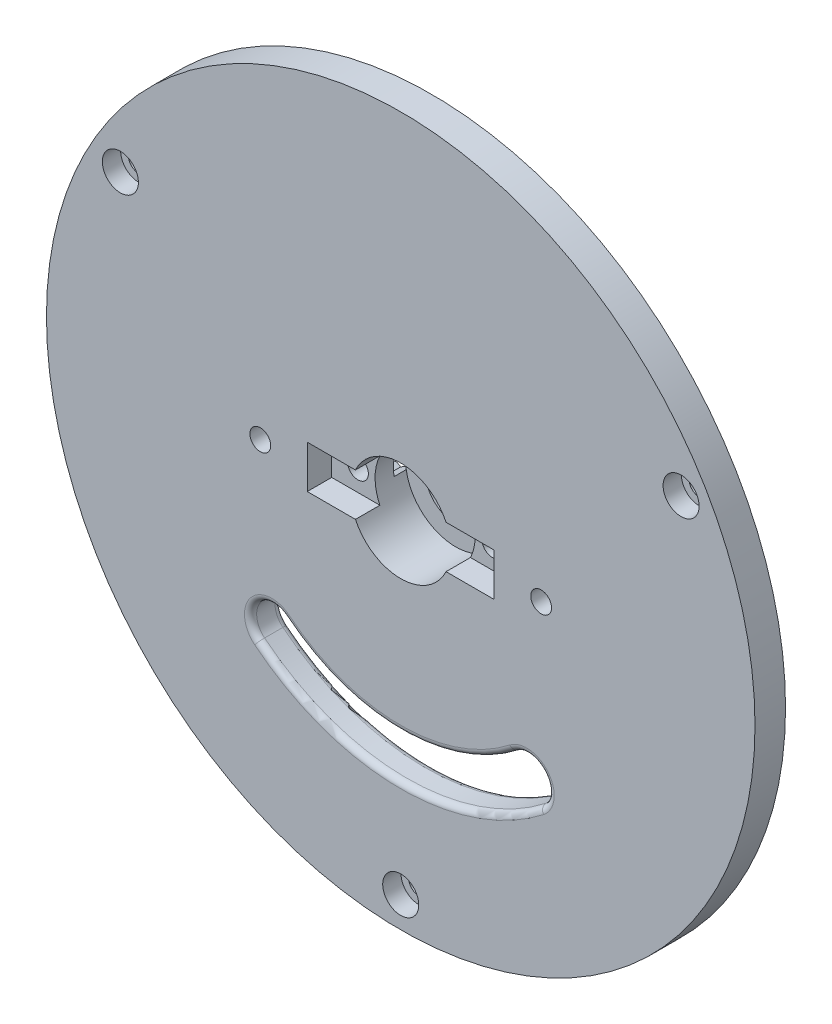
SolidWorks part; units mm, degrees
ref_plane "Front Plane" through (0, 0, 0) normal (0, 0, 1) x (1, 0, 0)
ref_plane "Top Plane" through (0, 0, 0) normal (0, 1, 0) x (1, 0, 0)
ref_plane "Right Plane" through (0, 0, 0) normal (1, 0, 0) x (0, 0, -1)
sketch "Sketch1" plane through (0, 0, 0) normal (0, 0, 1) x (1, 0, 0)
  line L0 (0, 0) -> (0, -68.2966) construction
  line L1 (0, 0) -> (-62.8311, 36.2756) construction
  circle A0 centre (0, 0) radius 8.2
  circle A1 centre (0, 53) radius 1.7 construction
  circle A2 centre (0, 0) radius 53 construction
  circle A3 centre (0, 0) radius 58
  circle A6 centre (0, -53) radius 1.7
  circle A7 centre (-45.8993, 26.5) radius 1.7
  circle A8 centre (45.8993, 26.5) radius 1.7
  circle A9 centre (-45.8993, 26.5) radius 1.7
  circle A10 centre (45.8993, 26.5) radius 1.7
  point P14 (0, 0)
  point P21 (0, 0)
  point P24 (0, 0)
  dimension "D1" = 16.4
  dimension "D2" = 106
  dimension "D3" = 3.4
  dimension "D4" = 5
  dimension "D5" = 120
  dimension "D6" = 3.4
  dimension "D8" = 106
  dimension "D7" = 3
  dimension "D9" = 3
extrude "Boss-Extrude1" add sketch "Sketch1" along normal blind 5
sketch "Sketch3" plane through (0, 0, 0) normal (0, 1, 0) x (1, 0, 0)
  line L0 (0, 0) -> (0, 9.41) construction
  line L2 (58, 0) -> (-58, 0) construction
  line L3 (-18, 0) -> (-12, 6)
  line L4 (-12, 6) -> (-5, 6)
  line L6 (-5, 6) -> (-5, 4)
  line L7 (-5, 4) -> (-8.2, 4)
  line L8 (-8.2, 4) -> (-8.2, 0)
  line L9 (-8.2, 0) -> (-18, 0)
  line L10 (-18.6622, -5) -> (0, -5)
  line L11 (-58, -5) -> (58, -5) construction
  dimension "D1" = 2
  dimension "D2" = 12
  dimension "D3" = 18
  dimension "D4" = 9
  dimension "D5" = 45
  dimension "D6" = 8.2
  dimension "D7" = 5
revolve "Revolve1" add sketch "Sketch3" angle 360 about L0
sketch "Sketch4" plane through (0, 0, 5) normal (0, 0, 1) x (1, 0, 0)
  line L1 (-15.3, 3.5) -> (15.3, 3.5)
  line L2 (-15.3, 3.5) -> (-15.3, -3.5)
  line L3 (-15.3, -3.5) -> (15.3, -3.5)
  line L4 (15.3, 3.5) -> (15.3, -3.5)
  line L5 (-15.3, 3.5) -> (15.3, -3.5) construction
  line L6 (-15.3, -3.5) -> (15.3, 3.5) construction
  point P0 (0, 0)
  dimension "D1" = 7
  dimension "D2" = 30.6
extrude "Cut-Extrude2" cut sketch "Sketch4" against normal blind 4
sketch "Sketch5" plane through (0, 0, -6) normal (0, 0, -1) x (-1, 0, 0)
  line L0 (-11, 0) -> (11, 0) construction
  line L1 (-13.9012, 1.675) -> (-11, 0) construction
  line L2 (-11, 0) -> (-8.0988, -1.675) construction
  line L3 (-13.9012, -1.675) -> (-8.0988, 1.675) construction
  line L4 (-11, -3.35) -> (-11, 3.35) construction
  line L11 (0, 0) -> (0, 11) construction
  line L18 (-11, 3.35) -> (-13.9012, 1.675)
  line L19 (-13.9012, 1.675) -> (-13.9012, -1.675)
  line L20 (-13.9012, -1.675) -> (-11, -3.35)
  line L21 (-11, -3.35) -> (-8.0988, -1.675)
  line L22 (-8.0988, -1.675) -> (-8.0988, 1.675)
  line L23 (-8.0988, 1.675) -> (-11, 3.35)
  line L24 (8.0988, -1.675) -> (8.0988, 1.675)
  line L25 (11, -3.35) -> (8.0988, -1.675)
  line L26 (13.9012, -1.675) -> (11, -3.35)
  line L27 (13.9012, 1.675) -> (13.9012, -1.675)
  line L28 (11, 3.35) -> (13.9012, 1.675)
  line L29 (8.0988, 1.675) -> (11, 3.35)
  circle A0 centre (0, 0) radius 11 construction
  circle A2 centre (-11, 0) radius 3.35 construction
  dimension "D1" = 22
  dimension "D2" = 6.7
  dimension "D3" = 60
  dimension "D4" = 60
extrude "Cut-Extrude3" cut sketch "Sketch5" against normal blind 4
sketch "Sketch6" plane through (0, 0, -6) normal (0, 0, -1) x (-1, 0, 0)
  circle A2 centre (0, 0) radius 11
  circle A3 centre (-11, 0) radius 1.7
  circle A4 centre (11, 0) radius 1.7
  dimension "D1" = 22
  dimension "D2" = 3.4
  dimension "D3" = 3.4
extrude "Cut-Extrude4" cut sketch "Sketch6" against normal through all contours A2 A3 | A2 A3 | A2 A4 | A2 A4
sketch "Sketch7" plane through (0, 0, 5) normal (0, 0, 1) x (1, 0, 0)
  circle A0 centre (-45.8993, -26.5) radius 2.95 construction
  circle A4 centre (0, 53) radius 2.95 construction
  circle A5 centre (45.8993, -26.5) radius 2.95 construction
  circle A6 centre (-45.8993, 26.5) radius 2.95
  circle A7 centre (45.8993, 26.5) radius 2.95
  circle A8 centre (0, -53) radius 2.95
  point P10 (0, 0)
  point P12 (0, 0)
  dimension "D1" = 5.9
  dimension "D3" = 5.9
  dimension "D4" = 5.9
  dimension "D5" = 5.9
  dimension "D2" = 3
extrude "Cut-Extrude5" cut sketch "Sketch7" against normal blind 3
sketch "Sketch8" plane through (0, 0, 5) normal (0, 0, 1) x (1, 0, 0)
  circle A1 centre (0, 0) radius 22.987 construction
  circle A2 centre (22.987, 0) radius 1.7
  circle A3 centre (-22.987, 0) radius 1.7
  dimension "D1" = 45.974
  dimension "D2" = 3.4
  dimension "D3" = 3.4
extrude "Cut-Extrude6" cut sketch "Sketch8" against normal through all
sketch "Sketch9" plane through (0, 0, -6) normal (0, 0, -1) x (-1, 0, 0)
  line L0 (-2.8844, 32.9686) -> (0, 0)
  line L1 (0, -54.7) -> (0, 0) construction
  line L2 (0, 0) -> (0, 33) construction
  line L3 (0, 0) -> (26.4894, 26.4894) construction
  line L4 (0, 0) -> (37.8104, -3.308)
  circle A0 centre (0, 0) radius 33
  circle A1 centre (0, 0) radius 32
  circle A2 centre (0, -53) radius 1.7 construction
  dimension "D3" = 64
  dimension "D1" = 66
  dimension "D2" = 135
  dimension "D4" = 50
  dimension "D5" = 50
extrude "Boss-Extrude2" add sketch "Sketch9" against normal blind 10 and the other way blind 3 contours A1 L4 A0 L0
sketch "Sketch10" plane through (0, 0, 5) normal (0, 0, 1) x (1, 0, 0)
  line L0 (0, 0) -> (25.7024, -26.6156)
  line L1 (0, 0) -> (37, 0) construction
  line L2 (0, 0) -> (-26.163, -26.163)
  line L3 (0, 0) -> (0, -37) construction
  line L4 (0, 0) -> (0, -37) construction
  circle A0 centre (0, 0) radius 30
  circle A1 centre (0, 0) radius 37
  circle A3 centre (-21.0836, -26.0333) radius 3.5
  circle A4 centre (0, 0) radius 33.5 construction
  circle A5 centre (20.626, -26.3973) radius 3.5
  line M13 (-15.3, 3.5) -> (-7.4155, 3.5)
  dimension "D1" = 60
  dimension "D3" = 7
  dimension "D2" = 7
  dimension "D4" = 3.5
  dimension "D5" = 7
  dimension "D6" = 0
  dimension "D7" = 44
  dimension "D8" = 45
extrude "Cut-Extrude7" cut sketch "Sketch10" along normal through all and the other way through all contours A3 | A0 A5 A1 A3 | A5 M13
fillet "Fillet1" radius 1 8 edges at (-23.8035, -23.8306, 5) (-0.3229, -36.9986, 5) (23.3839, -24.2423, 5) (-23.8035, -23.8306, 0) (-0.3229, -36.9986, 0) (23.3839, -24.2423, 0) (-0.2618, -29.9989, 5) (-0.2618, -29.9989, 0)
sketch "Sketch11" plane through (0, 0, 0) normal (0, 0, -1) x (-1, 0, 0)
  line L0 (0, 0) -> (0, 20.7109) construction
  line L1 (-26.337, 0) -> (-19.637, 0) construction
  line L2 (-21.312, 2.9012) -> (-24.662, -2.9012) construction
  line L3 (-24.662, 2.9012) -> (-21.312, -2.9012) construction
  line L4 (-24.662, 2.9012) -> (-26.337, 0)
  line L5 (-26.337, 0) -> (-24.662, -2.9012)
  line L6 (-24.662, -2.9012) -> (-21.312, -2.9012)
  line L7 (-21.312, -2.9012) -> (-19.637, 0)
  line L8 (-19.637, 0) -> (-21.312, 2.9012)
  line L9 (-21.312, 2.9012) -> (-24.662, 2.9012)
  line L10 (19.637, 0) -> (21.312, 2.9012)
  line L11 (21.312, -2.9012) -> (19.637, 0)
  line L12 (24.662, -2.9012) -> (21.312, -2.9012)
  line L13 (26.337, 0) -> (24.662, -2.9012)
  line L14 (24.662, 2.9012) -> (26.337, 0)
  line L15 (21.312, 2.9012) -> (24.662, 2.9012)
  circle A1 centre (-22.987, 0) radius 3.35 construction
  circle A2 centre (-22.987, 0) radius 7
  circle A3 centre (22.987, 0) radius 7
  dimension "D1" = 6.7
  dimension "D2" = 60
  dimension "D4" = 14
  dimension "D3" = 60
extrude "Boss-Extrude3" add sketch "Sketch11" along normal blind 3
